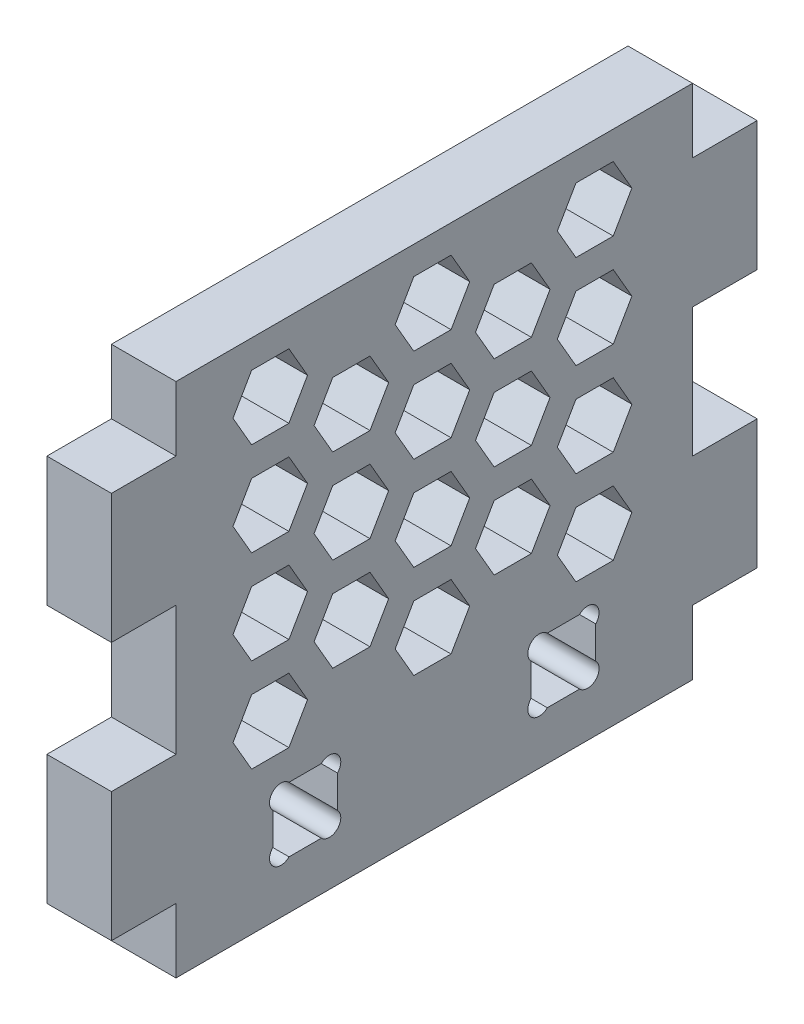
SolidWorks part; units mm, degrees
material "6061 Alloy"
ref_plane "Front" through (0, 0, 0) normal (0, 0, 1) x (1, 0, 0)
ref_plane "Top" through (0, 0, 0) normal (0, 1, 0) x (1, 0, 0)
ref_plane "Right" through (0, 0, 0) normal (1, 0, 0) x (0, 0, -1)
sketch "Sketch3" plane through (0, 0, 0) normal (1, 0, 0) x (0, 0, -1)
  line L1 (-50.8, -50.8) -> (50.8, -50.8)
  line L2 (-50.8, -50.8) -> (-50.8, 50.8)
  line L3 (-50.8, 50.8) -> (50.8, 50.8)
  line L4 (50.8, -50.8) -> (50.8, 50.8)
  line L5 (-50.8, -50.8) -> (50.8, 50.8) construction
  line L6 (-50.8, 50.8) -> (50.8, -50.8) construction
  point P0 (0, 0)
  dimension "D1" = 101.6
  dimension "D2" = 101.6
extrude "Square Extrusion" add sketch "Sketch3" along normal blind 12.7
sketch "Sketch4" plane through (12.7, 0, 0) normal (1, 0, 0) x (0, 0, -1)
  line L0 (-50.8, -50.8) -> (-25.4, -50.8) construction
  line L1 (-50.8, -50.8) -> (50.8, -50.8) construction
  line L2 (-25.4, -50.8) -> (-25.4, -34.925) construction
  line L3 (0, -50.8) -> (0, 50.8) construction
  line L4 (-31.75, -41.275) -> (-19.05, -41.275)
  line L5 (-31.75, -41.275) -> (-31.75, -28.575)
  line L6 (-31.75, -28.575) -> (-19.05, -28.575)
  line L7 (-19.05, -41.275) -> (-19.05, -28.575)
  line L8 (-31.75, -41.275) -> (-19.05, -28.575) construction
  line L9 (-31.75, -28.575) -> (-19.05, -41.275) construction
  line L10 (50.8, 50.8) -> (-50.8, 50.8) construction
  line L11 (31.75, -28.575) -> (19.05, -28.575)
  line L12 (19.05, -41.275) -> (19.05, -28.575)
  line L13 (31.75, -41.275) -> (19.05, -41.275)
  line L14 (31.75, -41.275) -> (31.75, -28.575)
  line L15 (-31.75, -34.925) -> (-19.05, -34.925) construction
  circle A0 centre (-20.6375, -30.1625) radius 2.2454
  circle A1 centre (-30.1625, -30.1625) radius 2.2454
  circle A2 centre (-20.6375, -39.6875) radius 2.2454
  circle A3 centre (-30.1625, -39.6875) radius 2.2454
  circle A4 centre (30.1625, -39.6875) radius 2.2454
  circle A5 centre (20.6375, -39.6875) radius 2.2454
  circle A6 centre (20.6375, -30.1625) radius 2.2454
  circle A7 centre (30.1625, -30.1625) radius 2.2454
  dimension "D7" = 4.4907
  dimension "D1" = 25.4
  dimension "D2" = 9.525
  dimension "D3" = 12.7
  dimension "D4" = 12.7
  dimension "D5" = 1.5875
extrude "Slotting Holes" cut sketch "Sketch4" against normal up to surface (12.7 mm away) contours A1 L5 L6 | A1 L6 L5 | A3 L4 A2 L7 A0 L6 A1 L5 | L6 A0 L7 | L7 A0 L6 | L4 A3 L5 | L5 A3 L4 | A2 L4 L7 | A2 L7 L4 | A6 L12 L11 | A6 L11 L12 | A7 L11 A6 L12 A5 L13 A4 L14 | L11 A7 L14 | L14 A7 L11 | A4 L13 L14 | A4 L14 L13 | L13 A5 L12 | L12 A5 L13 up to face at (0, 0, 0)
sketch "Sketch9" plane through (12.7, 0, 0) normal (1, 0, 0) x (0, 0, -1)
  line L96 (0, 0) -> (0, 11.43) construction
  line L97 (0, 6.985) -> (0, -6.985) construction
  line L111 (6.9677, 38.9312) -> (3.3015, 45.2812)
  line L112 (-24.9281, 38.9312) -> (-28.5942, 45.2812)
  line L113 (-28.5942, 45.2812) -> (-35.9266, 45.2812)
  line L114 (-35.9266, 45.2812) -> (-39.5928, 38.9312)
  line L115 (-39.5928, 38.9312) -> (-35.9266, 32.5812)
  line L116 (-35.9266, 32.5812) -> (-28.5942, 32.5812)
  line L117 (-28.5942, 32.5812) -> (-24.9281, 38.9312)
  line L118 (3.3015, 45.2812) -> (-4.0309, 45.2812)
  line L119 (-4.0309, 45.2812) -> (-7.697, 38.9312)
  line L120 (-7.697, 38.9312) -> (-4.0309, 32.5812)
  line L121 (-4.0309, 32.5812) -> (3.3015, 32.5812)
  line L122 (3.3015, 32.5812) -> (6.9677, 38.9312)
  line L123 (38.8634, 38.9312) -> (35.1972, 45.2812)
  line L124 (35.1972, 45.2812) -> (27.8648, 45.2812)
  line L125 (27.8648, 45.2812) -> (24.1987, 38.9312)
  line L126 (24.1987, 38.9312) -> (27.8648, 32.5812)
  line L127 (27.8648, 32.5812) -> (35.1972, 32.5812)
  line L128 (35.1972, 32.5812) -> (38.8634, 38.9312)
  line L129 (-8.9802, 29.7237) -> (-12.6464, 36.0737)
  line L130 (-12.6464, 36.0737) -> (-19.9787, 36.0737)
  line L131 (-19.9787, 36.0737) -> (-23.6449, 29.7237)
  line L132 (-23.6449, 29.7237) -> (-19.9787, 23.3737)
  line L133 (-19.9787, 23.3737) -> (-12.6464, 23.3737)
  line L134 (-12.6464, 23.3737) -> (-8.9802, 29.7237)
  line L135 (22.7698, 29.7237) -> (19.1036, 36.0737)
  line L136 (19.1036, 36.0737) -> (11.7713, 36.0737)
  line L137 (11.7713, 36.0737) -> (8.1051, 29.7237)
  line L138 (8.1051, 29.7237) -> (11.7713, 23.3737)
  line L139 (11.7713, 23.3737) -> (19.1036, 23.3737)
  line L140 (19.1036, 23.3737) -> (22.7698, 29.7237)
  line L141 (-24.9281, 20.5162) -> (-28.5942, 26.8662)
  line L142 (-28.5942, 26.8662) -> (-35.9266, 26.8662)
  line L143 (-35.9266, 26.8662) -> (-39.5928, 20.5162)
  line L144 (-39.5928, 20.5162) -> (-35.9266, 14.1662)
  line L145 (-35.9266, 14.1662) -> (-28.5942, 14.1662)
  line L146 (-28.5942, 14.1662) -> (-24.9281, 20.5162)
  line L147 (6.9677, 20.5162) -> (3.3015, 26.8662)
  line L148 (3.3015, 26.8662) -> (-4.0309, 26.8662)
  line L149 (-4.0309, 26.8662) -> (-7.697, 20.5162)
  line L150 (-7.697, 20.5162) -> (-4.0309, 14.1662)
  line L151 (-4.0309, 14.1662) -> (3.3015, 14.1662)
  line L152 (3.3015, 14.1662) -> (6.9677, 20.5162)
  line L153 (38.8634, 20.5162) -> (35.1972, 26.8662)
  line L154 (35.1972, 26.8662) -> (27.8648, 26.8662)
  line L155 (27.8648, 26.8662) -> (24.1987, 20.5162)
  line L156 (24.1987, 20.5162) -> (27.8648, 14.1662)
  line L157 (27.8648, 14.1662) -> (35.1972, 14.1662)
  line L158 (35.1972, 14.1662) -> (38.8634, 20.5162)
  line L159 (-24.9281, 2.1012) -> (-28.5942, 8.4512)
  line L160 (-28.5942, 8.4512) -> (-35.9266, 8.4512)
  line L161 (-35.9266, 8.4512) -> (-39.5928, 2.1012)
  line L162 (-39.5928, 2.1012) -> (-35.9266, -4.2488)
  line L163 (-35.9266, -4.2488) -> (-28.5942, -4.2488)
  line L164 (-28.5942, -4.2488) -> (-24.9281, 2.1012)
  line L165 (-8.9802, -7.1063) -> (-12.6464, -0.7563)
  line L166 (-12.6464, -0.7563) -> (-19.9787, -0.7563)
  line L167 (-19.9787, -0.7563) -> (-23.6449, -7.1063)
  line L168 (-23.6449, -7.1063) -> (-19.9787, -13.4563)
  line L169 (-19.9787, -13.4563) -> (-12.6464, -13.4563)
  line L170 (-12.6464, -13.4563) -> (-8.9802, -7.1063)
  line L171 (6.9677, 2.1012) -> (3.3015, 8.4512)
  line L172 (3.3015, 8.4512) -> (-4.0309, 8.4512)
  line L173 (-4.0309, 8.4512) -> (-7.697, 2.1012)
  line L174 (-7.697, 2.1012) -> (-4.0309, -4.2488)
  line L175 (-4.0309, -4.2488) -> (3.3015, -4.2488)
  line L176 (3.3015, -4.2488) -> (6.9677, 2.1012)
  line L177 (22.7698, -7.1063) -> (19.1036, -0.7563)
  line L178 (19.1036, -0.7563) -> (11.7713, -0.7563)
  line L179 (11.7713, -0.7563) -> (8.1051, -7.1063)
  line L180 (8.1051, -7.1063) -> (11.7713, -13.4563)
  line L181 (11.7713, -13.4563) -> (19.1036, -13.4563)
  line L182 (19.1036, -13.4563) -> (22.7698, -7.1063)
  line L183 (38.8634, 2.1012) -> (35.1972, 8.4512)
  line L184 (35.1972, 8.4512) -> (27.8648, 8.4512)
  line L185 (27.8648, 8.4512) -> (24.1987, 2.1012)
  line L186 (24.1987, 2.1012) -> (27.8648, -4.2488)
  line L187 (27.8648, -4.2488) -> (35.1972, -4.2488)
  line L188 (35.1972, -4.2488) -> (38.8634, 2.1012)
  line L189 (38.8634, -16.3138) -> (35.1972, -9.9638)
  line L190 (35.1972, -9.9638) -> (27.8648, -9.9638)
  line L191 (27.8648, -9.9638) -> (24.1987, -16.3138)
  line L192 (24.1987, -16.3138) -> (27.8648, -22.6638)
  line L193 (27.8648, -22.6638) -> (35.1972, -22.6638)
  line L194 (35.1972, -22.6638) -> (38.8634, -16.3138)
  line L195 (6.9677, -16.3138) -> (3.3015, -9.9638)
  line L196 (-4.0309, -9.9638) -> (-7.697, -16.3138)
  line L197 (-7.697, -16.3138) -> (-4.0309, -22.6638)
  line L198 (-4.0309, -22.6638) -> (3.3015, -22.6638)
  line L199 (3.3015, -22.6638) -> (6.9677, -16.3138)
  line L200 (3.3015, -9.9638) -> (-4.0309, -9.9638)
  line L201 (-24.9281, -16.3138) -> (-28.5942, -9.9638)
  line L202 (-28.5942, -9.9638) -> (-35.9266, -9.9638)
  line L203 (-35.9266, -9.9638) -> (-39.5928, -16.3138)
  line L204 (-39.5928, -16.3138) -> (-35.9266, -22.6638)
  line L205 (-35.9266, -22.6638) -> (-28.5942, -22.6638)
  line L206 (-28.5942, -22.6638) -> (-24.9281, -16.3138)
  line L207 (22.7698, 11.3087) -> (19.1036, 17.6587)
  line L208 (19.1036, 17.6587) -> (11.7713, 17.6587)
  line L209 (11.7713, 17.6587) -> (8.1051, 11.3087)
  line L210 (8.1051, 11.3087) -> (11.7713, 4.9587)
  line L211 (11.7713, 4.9587) -> (19.1036, 4.9587)
  line L212 (19.1036, 4.9587) -> (22.7698, 11.3087)
  line L213 (-8.9802, 11.3087) -> (-12.6464, 17.6587)
  line L214 (-12.6464, 17.6587) -> (-19.9787, 17.6587)
  line L215 (-19.9787, 17.6587) -> (-23.6449, 11.3087)
  line L216 (-23.6449, 11.3087) -> (-19.9787, 4.9587)
  line L217 (-19.9787, 4.9587) -> (-12.6464, 4.9587)
  line L218 (-12.6464, 4.9587) -> (-8.9802, 11.3087)
  circle A0 centre (-32.2604, 38.9312) radius 6.35 construction
  circle A1 centre (-0.3647, 38.9312) radius 6.35 construction
  circle A2 centre (31.531, 38.9312) radius 6.35 construction
  circle A3 centre (-16.3126, 29.7237) radius 6.35 construction
  circle A4 centre (15.4374, 29.7237) radius 6.35 construction
  circle A5 centre (-32.2604, 20.5162) radius 6.35 construction
  circle A6 centre (-0.3647, 20.5162) radius 6.35 construction
  circle A7 centre (31.531, 20.5162) radius 6.35 construction
  circle A8 centre (-32.2604, 2.1012) radius 6.35 construction
  circle A9 centre (-16.3126, -7.1063) radius 6.35 construction
  circle A10 centre (-0.3647, 2.1012) radius 6.35 construction
  circle A11 centre (15.4374, -7.1063) radius 6.35 construction
  circle A12 centre (31.531, 2.1012) radius 6.35 construction
  circle A13 centre (31.531, -16.3138) radius 6.35 construction
  circle A14 centre (-0.3647, -16.3138) radius 6.35 construction
  circle A15 centre (-32.2604, -16.3138) radius 6.35 construction
  circle A16 centre (-16.3126, 11.3087) radius 6.35 construction
  circle A17 centre (15.4374, 11.3087) radius 6.35 construction
  dimension "D1" = 11.43
extrude "Honeycomb Pocketing" cut sketch "Sketch9" against normal up to surface (12.7 mm away) up to face at (0, -34.925, 25.4)
sketch "Sketch10" plane through (12.7, 0, 0) normal (1, 0, 0) x (0, 0, -1)
  line L0 (-50.8, 0) -> (50.8, 0) construction
  line L1 (-50.8, 0) -> (-50.8, 50.8) construction
  line L2 (-50.8, 25.4) -> (-63.5, 25.4)
  line L3 (-50.8, 25.4) -> (-50.8, 38.1)
  line L4 (-50.8, 38.1) -> (-63.5, 38.1)
  line L5 (-63.5, 25.4) -> (-63.5, 38.1)
  line L6 (-63.5, 25.4) -> (-50.8, 25.4)
  line L7 (-63.5, 25.4) -> (-63.5, 12.7)
  line L8 (-63.5, 12.7) -> (-50.8, 12.7)
  line L9 (-50.8, 25.4) -> (-50.8, 12.7)
  line L10 (50.8, -50.8) -> (50.8, 50.8) construction
  line L11 (-63.5, -12.7) -> (-50.8, -12.7)
  line L12 (-50.8, -25.4) -> (-50.8, -12.7)
  line L13 (-63.5, -25.4) -> (-50.8, -25.4)
  line L14 (-63.5, -25.4) -> (-63.5, -12.7)
  line L15 (-50.8, -38.1) -> (-63.5, -38.1)
  line L16 (-63.5, -25.4) -> (-63.5, -38.1)
  line L17 (-50.8, -25.4) -> (-63.5, -25.4)
  line L18 (-50.8, -25.4) -> (-50.8, -38.1)
  line L19 (0, 50.8) -> (0, -50.8) construction
  line L20 (50.8, 50.8) -> (-50.8, 50.8) construction
  line L21 (-50.8, -50.8) -> (50.8, -50.8) construction
  line L22 (50.8, -38.1) -> (63.5, -38.1)
  line L23 (63.5, -25.4) -> (63.5, -38.1)
  line L24 (63.5, -25.4) -> (50.8, -25.4)
  line L25 (63.5, -25.4) -> (63.5, -12.7)
  line L26 (63.5, -12.7) -> (50.8, -12.7)
  line L27 (50.8, -25.4) -> (50.8, -12.7)
  line L28 (50.8, -25.4) -> (50.8, -38.1)
  line L29 (63.5, 12.7) -> (50.8, 12.7)
  line L30 (50.8, 25.4) -> (50.8, 12.7)
  line L31 (63.5, 25.4) -> (50.8, 25.4)
  line L32 (63.5, 25.4) -> (63.5, 12.7)
  line L33 (50.8, 38.1) -> (63.5, 38.1)
  line L34 (63.5, 25.4) -> (63.5, 38.1)
  line L35 (50.8, 25.4) -> (63.5, 25.4)
  line L36 (50.8, 25.4) -> (50.8, 38.1)
  dimension "D1" = 12.7
  dimension "D2" = 12.7
  dimension "D3" = 12.7
extrude "Side Slots" add sketch "Sketch10" against normal blind 12.7 contours L5 L2 L3 L4 | L9 L2 L7 L8 | L14 L13 L12 L11 | L18 L13 L16 L15 | L27 L24 L25 L26 | L24 L28 L22 L23 | L32 L31 L30 L29 | L36 L31 L34 L33
